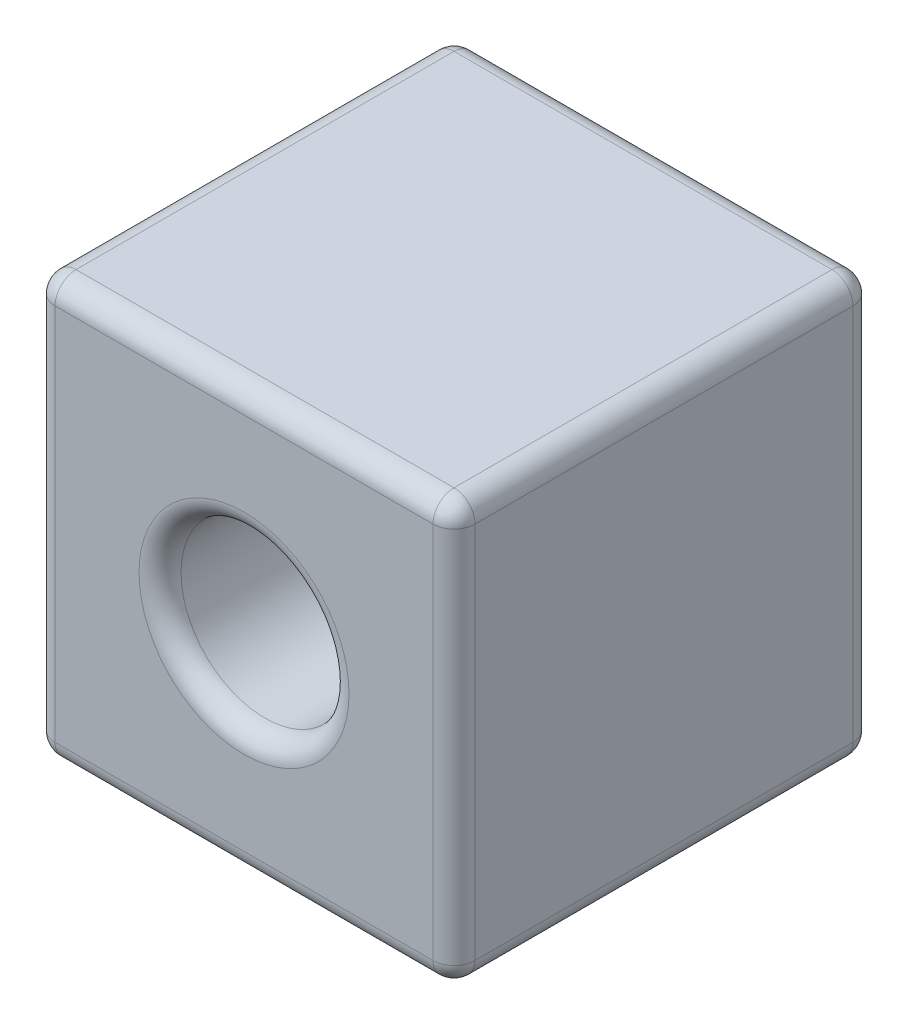
SolidWorks part; units mm, degrees
ref_plane "前视基准面" through (0, 0, 0) normal (0, 0, 1) x (1, 0, 0)
ref_plane "上视基准面" through (0, 0, 0) normal (0, 1, 0) x (1, 0, 0)
ref_plane "右视基准面" through (0, 0, 0) normal (1, 0, 0) x (0, 0, -1)
sketch "草图1" plane through (0, 0, 0) normal (0, 0, 1) x (1, 0, 0)
  line L1 (-50, 50) -> (50, 50)
  line L2 (-50, 50) -> (-50, -50)
  line L3 (-50, -50) -> (50, -50)
  line L4 (50, 50) -> (50, -50)
  line L5 (-50, 50) -> (50, -50) construction
  line L6 (-50, -50) -> (50, 50) construction
  circle A0 centre (0, 0) radius 20
  point P0 (0, 0)
  dimension "D2" = 40
  dimension "D1" = 100
extrude "凸台-拉伸1" add sketch "草图1" along normal blind 100
fillet "圆角1" radius 5 12 edges at (0, 50, 0) (-50, 50, 50) (-50, 0, 0) (0, -50, 0) (-50, -50, 50) (-50, 0, 100) (0, 50, 100) (50, 50, 50) (50, 0, 0) (50, -50, 50) (50, 0, 100) (0, -50, 100)
fillet "圆角2" radius 5 2 edges at (20, 0, 0) (20, 0, 100)
